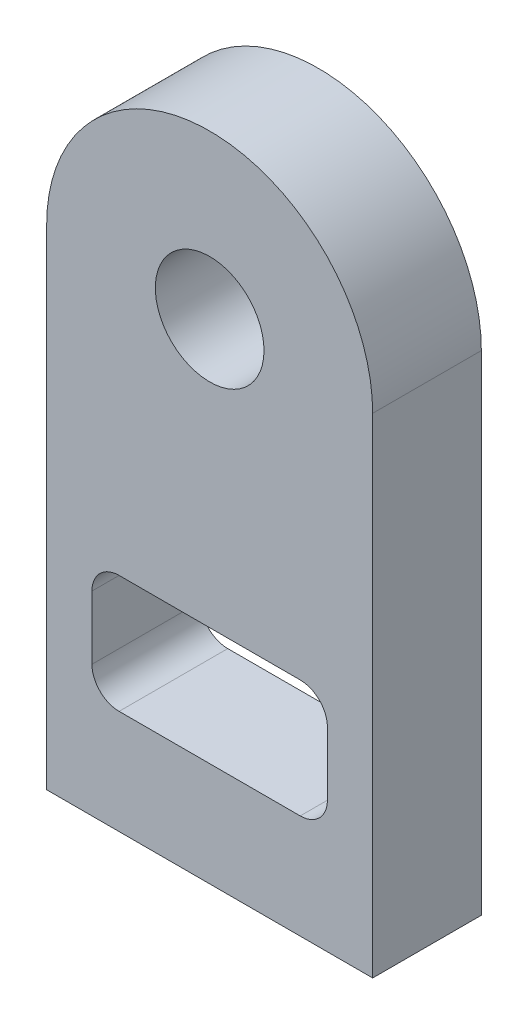
SolidWorks part; units mm, degrees
ref_plane "Alzado" through (0, 0, 0) normal (0, 0, 1) x (1, 0, 0)
ref_plane "Planta" through (0, 0, 0) normal (0, 1, 0) x (1, 0, 0)
ref_plane "Vista lateral" through (0, 0, 0) normal (1, 0, 0) x (0, 0, -1)
sketch "Model" plane through (0, 0, 0) normal (0, 0, 1) x (1, 0, 0)
  line L0 (159.5914, 212.494) -> (159.5914, 198.994)
  line L1 (159.5914, 198.994) -> (150.5914, 198.994)
  line L2 (150.5914, 198.994) -> (150.5914, 212.494)
  line L3 (157.5914, 201.869) -> (152.5914, 201.869)
  line L4 (151.8414, 202.619) -> (151.8414, 204.369)
  line L5 (152.5914, 205.119) -> (157.5914, 205.119)
  line L6 (158.3414, 204.369) -> (158.3414, 202.619)
  circle A0 centre (155.0914, 212.494) radius 1.5
  arc A1 (159.5914, 212.494) -> (150.5914, 212.494) centre (155.0914, 212.494) ccw
  arc A2 (151.8414, 202.619) -> (152.5914, 201.869) centre (152.5914, 202.619) ccw
  arc A3 (152.5914, 205.119) -> (151.8414, 204.369) centre (152.5914, 204.369) ccw
  arc A4 (158.3414, 204.369) -> (157.5914, 205.119) centre (157.5914, 204.369) ccw
  arc A5 (157.5914, 201.869) -> (158.3414, 202.619) centre (157.5914, 202.619) ccw
extrude "Saliente-Extruir1" add sketch "Model" along normal blind 3
